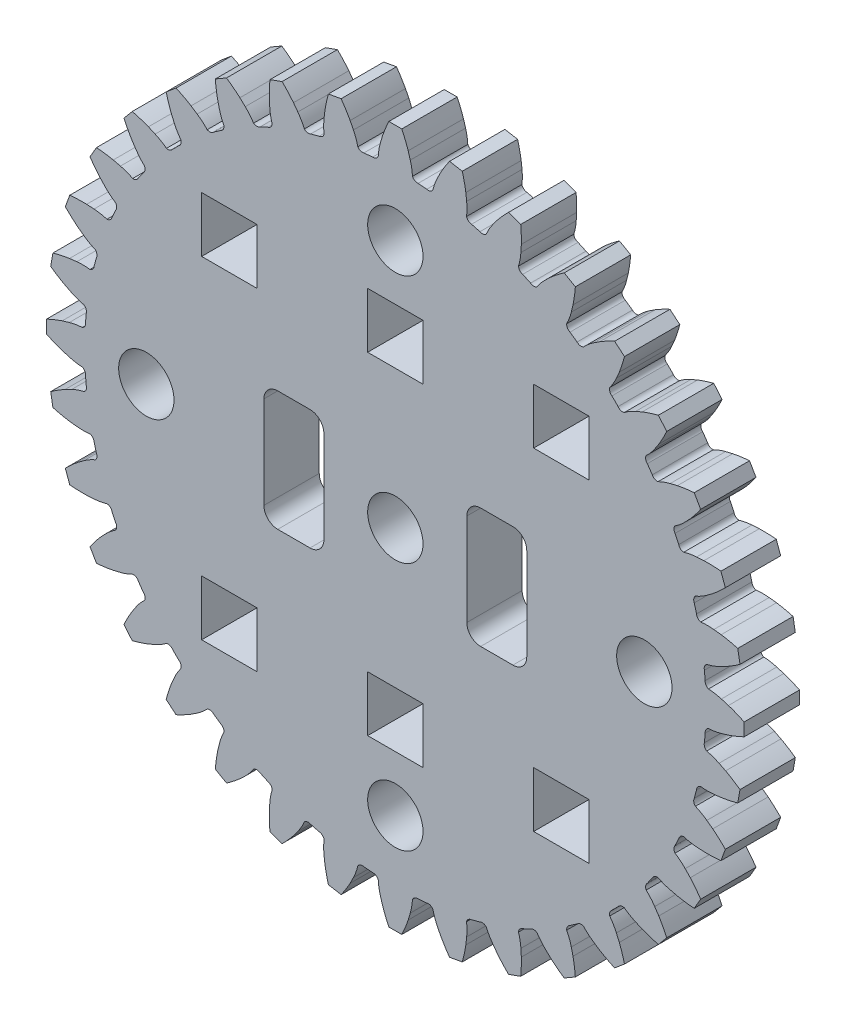
SolidWorks part; units mm, degrees
ref_plane "Alzado" through (0, 0, 0) normal (0, 0, 1) x (1, 0, 0)
ref_plane "Planta" through (0, 0, 0) normal (0, 1, 0) x (1, 0, 0)
ref_plane "Vista lateral" through (0, 0, 0) normal (1, 0, 0) x (0, 0, -1)
sketch "Model" plane through (0, 0, 0) normal (0, 0, 1) x (1, 0, 0)
  line L0 (33.2182, 284.4472) -> (33.2182, 281.4472)
  line L1 (36.2182, 284.4472) -> (33.2182, 284.4472)
  line L2 (36.2182, 281.4472) -> (36.2182, 284.4472)
  line L3 (33.2182, 281.4472) -> (36.2182, 281.4472)
  line L4 (15.2182, 284.4472) -> (15.2182, 281.4472)
  line L5 (18.2182, 284.4472) -> (15.2182, 284.4472)
  line L6 (18.2182, 281.4472) -> (18.2182, 284.4472)
  line L7 (15.2182, 281.4472) -> (18.2182, 281.4472)
  line L8 (24.2182, 284.4472) -> (24.2182, 281.4472)
  line L9 (27.2182, 284.4472) -> (24.2182, 284.4472)
  line L10 (27.2182, 281.4472) -> (27.2182, 284.4472)
  line L11 (24.2182, 281.4472) -> (27.2182, 281.4472)
  line L12 (33.2182, 266.4472) -> (33.2182, 263.4472)
  line L13 (36.2182, 266.4472) -> (33.2182, 266.4472)
  line L14 (36.2182, 263.4472) -> (36.2182, 266.4472)
  line L15 (33.2182, 263.4472) -> (36.2182, 263.4472)
  line L16 (15.2182, 266.4472) -> (15.2182, 263.4472)
  line L17 (18.2182, 266.4472) -> (15.2182, 266.4472)
  line L18 (18.2182, 263.4472) -> (18.2182, 266.4472)
  line L19 (15.2182, 263.4472) -> (18.2182, 263.4472)
  line L20 (24.2182, 266.4472) -> (24.2182, 263.4472)
  line L21 (27.2182, 266.4472) -> (24.2182, 266.4472)
  line L22 (27.2182, 263.4472) -> (27.2182, 266.4472)
  line L23 (24.2182, 263.4472) -> (27.2182, 263.4472)
  line L24 (31.0032, 290.8357) -> (31.2404, 291.1562)
  line L25 (31.8576, 291.8382) -> (32.5152, 291.5989)
  line L26 (32.5496, 290.6797) -> (32.5254, 290.2817)
  line L27 (32.6219, 289.3103) -> (33.0493, 289.111)
  line L28 (33.8556, 289.6614) -> (34.1448, 289.9358)
  line L29 (34.8711, 290.5003) -> (35.4771, 290.1504)
  line L30 (35.3514, 289.2392) -> (35.2584, 288.8515)
  line L31 (35.1848, 287.878) -> (35.5711, 287.6076)
  line L32 (36.4607, 288.0097) -> (36.7932, 288.2296)
  line L33 (37.6064, 288.6595) -> (38.1425, 288.2096)
  line L34 (37.8605, 287.3341) -> (37.7016, 286.9684)
  line L35 (37.4601, 286.0225) -> (37.7935, 285.6891)
  line L36 (38.7394, 285.9306) -> (39.1051, 286.0895)
  line L37 (39.9806, 286.3716) -> (40.4304, 285.8355)
  line L38 (40.0006, 285.0222) -> (39.7806, 284.6897)
  line L39 (39.3785, 283.8001) -> (39.649, 283.4138)
  line L40 (40.6225, 283.4874) -> (41.0102, 283.5804)
  line L41 (41.9214, 283.7062) -> (42.2713, 283.1001)
  line L42 (41.7068, 282.3739) -> (41.4324, 282.0846)
  line L43 (40.882, 281.2783) -> (41.0812, 280.851)
  line L44 (42.0527, 280.7544) -> (42.4507, 280.7786)
  line L45 (43.3699, 280.7442) -> (43.6092, 280.0866)
  line L46 (42.9272, 279.4694) -> (42.6067, 279.2322)
  line L47 (41.9246, 278.5338) -> (42.0467, 278.0783)
  line L48 (42.9866, 277.8145) -> (43.3827, 277.7693)
  line L49 (44.282, 277.5758) -> (44.4035, 276.8866)
  line L50 (43.6247, 276.3972) -> (43.2679, 276.2192)
  line L51 (42.4749, 275.6499) -> (42.516, 275.1801)
  line L52 (43.3958, 274.7571) -> (43.7781, 274.6438)
  line L53 (44.6301, 274.2971) -> (44.6301, 273.5973)
  line L54 (43.7781, 273.2506) -> (43.3958, 273.1373)
  line L55 (42.516, 272.7142) -> (42.4749, 272.2445)
  line L56 (43.2679, 271.6751) -> (43.6247, 271.4971)
  line L57 (44.4035, 271.0078) -> (44.282, 270.3186)
  line L58 (43.3827, 270.1251) -> (42.9866, 270.0799)
  line L59 (42.0467, 269.8161) -> (41.9246, 269.3606)
  line L60 (42.6067, 268.6622) -> (42.9272, 268.4249)
  line L61 (43.6092, 267.8077) -> (43.3699, 267.1501)
  line L62 (42.4507, 267.1157) -> (42.0527, 267.14)
  line L63 (41.0812, 267.0434) -> (40.882, 266.616)
  line L64 (41.4324, 265.8098) -> (41.7068, 265.5205)
  line L65 (42.2713, 264.7943) -> (41.9214, 264.1882)
  line L66 (41.0102, 264.3139) -> (40.6225, 264.4069)
  line L67 (39.649, 264.4805) -> (39.3785, 264.0942)
  line L68 (39.7806, 263.2047) -> (40.0006, 262.8721)
  line L69 (40.4304, 262.0589) -> (39.9806, 261.5228)
  line L70 (39.1051, 261.8049) -> (38.7394, 261.9638)
  line L71 (37.7935, 262.2053) -> (37.4601, 261.8718)
  line L72 (37.7016, 260.9259) -> (37.8605, 260.5603)
  line L73 (38.1425, 259.6847) -> (37.6064, 259.2349)
  line L74 (36.7932, 259.6647) -> (36.4607, 259.8847)
  line L75 (35.5711, 260.2868) -> (35.1848, 260.0163)
  line L76 (35.2584, 259.0429) -> (35.3514, 258.6552)
  line L77 (35.4771, 257.744) -> (34.8711, 257.394)
  line L78 (34.1448, 257.9585) -> (33.8556, 258.2329)
  line L79 (33.0493, 258.7834) -> (32.6219, 258.5841)
  line L80 (32.5254, 257.6127) -> (32.5496, 257.2147)
  line L81 (32.5152, 256.2955) -> (31.8576, 256.0561)
  line L82 (31.2404, 256.7382) -> (31.0032, 257.0586)
  line L83 (30.3048, 257.7407) -> (29.8493, 257.6187)
  line L84 (29.5855, 256.6788) -> (29.5403, 256.2826)
  line L85 (29.3468, 255.3834) -> (28.6576, 255.2618)
  line L86 (28.1682, 256.0407) -> (27.9902, 256.3975)
  line L87 (27.4209, 257.1905) -> (26.9511, 257.1494)
  line L88 (26.5281, 256.2695) -> (26.4148, 255.8873)
  line L89 (26.0681, 255.0353) -> (25.3682, 255.0353)
  line L90 (25.0215, 255.8873) -> (24.9082, 256.2695)
  line L91 (24.4852, 257.1494) -> (24.0155, 257.1905)
  line L92 (23.4461, 256.3975) -> (23.2681, 256.0407)
  line L93 (22.7787, 255.2618) -> (22.0895, 255.3834)
  line L94 (21.8961, 256.2826) -> (21.8508, 256.6788)
  line L95 (21.587, 257.6187) -> (21.1316, 257.7407)
  line L96 (20.4331, 257.0586) -> (20.1959, 256.7382)
  line L97 (19.5787, 256.0561) -> (18.9211, 256.2955)
  line L98 (18.8867, 257.2147) -> (18.911, 257.6127)
  line L99 (18.8144, 258.5841) -> (18.387, 258.7834)
  line L100 (17.5808, 258.2329) -> (17.2915, 257.9585)
  line L101 (16.5652, 257.394) -> (15.9592, 257.744)
  line L102 (16.0849, 258.6552) -> (16.1779, 259.0429)
  line L103 (16.2515, 260.0163) -> (15.8652, 260.2868)
  line L104 (14.9756, 259.8847) -> (14.6431, 259.6647)
  line L105 (13.8299, 259.2349) -> (13.2938, 259.6847)
  line L106 (13.5758, 260.5603) -> (13.7347, 260.9259)
  line L107 (13.9762, 261.8718) -> (13.6428, 262.2053)
  line L108 (12.6969, 261.9638) -> (12.3312, 261.8049)
  line L109 (11.4557, 261.5228) -> (11.0059, 262.0589)
  line L110 (11.4357, 262.8721) -> (11.6557, 263.2047)
  line L111 (12.0578, 264.0942) -> (11.7873, 264.4805)
  line L112 (10.8138, 264.4069) -> (10.4261, 264.3139)
  line L113 (9.5149, 264.1882) -> (9.165, 264.7943)
  line L114 (9.7295, 265.5205) -> (10.0039, 265.8098)
  line L115 (10.5544, 266.616) -> (10.3551, 267.0434)
  line L116 (9.3836, 267.14) -> (8.9857, 267.1157)
  line L117 (8.0665, 267.1501) -> (7.8271, 267.8077)
  line L118 (8.5091, 268.4249) -> (8.8296, 268.6622)
  line L119 (9.5117, 269.3606) -> (9.3896, 269.8161)
  line L120 (8.4497, 270.0799) -> (8.0536, 270.1251)
  line L121 (7.1543, 270.3186) -> (7.0328, 271.0078)
  line L122 (7.8117, 271.4971) -> (8.1684, 271.6751)
  line L123 (8.9614, 272.2445) -> (8.9203, 272.7142)
  line L124 (8.0405, 273.1373) -> (7.6582, 273.2506)
  line L125 (6.8063, 273.5973) -> (6.8063, 274.2971)
  line L126 (7.6582, 274.6438) -> (8.0405, 274.7571)
  line L127 (8.9203, 275.1801) -> (8.9614, 275.6499)
  line L128 (8.1684, 276.2192) -> (7.8117, 276.3972)
  line L129 (7.0328, 276.8866) -> (7.1543, 277.5758)
  line L130 (8.0536, 277.7693) -> (8.4497, 277.8145)
  line L131 (9.3896, 278.0783) -> (9.5117, 278.5338)
  line L132 (8.8296, 279.2322) -> (8.5091, 279.4694)
  line L133 (7.8271, 280.0866) -> (8.0665, 280.7442)
  line L134 (8.9857, 280.7786) -> (9.3836, 280.7544)
  line L135 (10.3551, 280.851) -> (10.5544, 281.2783)
  line L136 (10.0039, 282.0846) -> (9.7295, 282.3739)
  line L137 (9.165, 283.1001) -> (9.5149, 283.7062)
  line L138 (10.4261, 283.5804) -> (10.8138, 283.4874)
  line L139 (11.7873, 283.4138) -> (12.0578, 283.8001)
  line L140 (11.6557, 284.6897) -> (11.4357, 285.0222)
  line L141 (11.0059, 285.8355) -> (11.4557, 286.3716)
  line L142 (12.3312, 286.0895) -> (12.6969, 285.9306)
  line L143 (13.6428, 285.6891) -> (13.9762, 286.0225)
  line L144 (13.7347, 286.9684) -> (13.5758, 287.3341)
  line L145 (13.2938, 288.2096) -> (13.8299, 288.6595)
  line L146 (14.6431, 288.2296) -> (14.9756, 288.0097)
  line L147 (15.8652, 287.6076) -> (16.2515, 287.878)
  line L148 (16.1779, 288.8515) -> (16.0849, 289.2392)
  line L149 (15.9592, 290.1504) -> (16.5652, 290.5003)
  line L150 (17.2915, 289.9358) -> (17.5808, 289.6614)
  line L151 (18.387, 289.111) -> (18.8144, 289.3103)
  line L152 (18.911, 290.2817) -> (18.8867, 290.6797)
  line L153 (18.9211, 291.5989) -> (19.5787, 291.8382)
  line L154 (20.1959, 291.1562) -> (20.4331, 290.8357)
  line L155 (21.1316, 290.1537) -> (21.587, 290.2757)
  line L156 (21.8508, 291.2156) -> (21.8961, 291.6118)
  line L157 (22.0895, 292.511) -> (22.7787, 292.6325)
  line L158 (23.2681, 291.8537) -> (23.4461, 291.4969)
  line L159 (24.0155, 290.7039) -> (24.4852, 290.745)
  line L160 (24.9082, 291.6248) -> (25.0215, 292.0071)
  line L161 (25.3682, 292.8591) -> (26.0681, 292.8591)
  line L162 (26.4148, 292.0071) -> (26.5281, 291.6248)
  line L163 (26.9511, 290.745) -> (27.4209, 290.7039)
  line L164 (27.9902, 291.4969) -> (28.1682, 291.8537)
  line L165 (28.6576, 292.6325) -> (29.3468, 292.511)
  line L166 (29.5403, 291.6118) -> (29.5855, 291.2156)
  line L167 (29.8493, 290.2757) -> (30.3048, 290.1537)
  line L168 (32.0932, 277.1972) -> (30.3432, 277.1972)
  line L169 (32.8432, 271.4472) -> (32.8432, 276.4472)
  line L170 (30.3432, 270.6972) -> (32.0932, 270.6972)
  line L171 (29.5932, 276.4472) -> (29.5932, 271.4472)
  line L172 (19.3432, 277.1972) -> (21.0932, 277.1972)
  line L173 (18.5932, 271.4472) -> (18.5932, 276.4472)
  line L174 (21.0932, 270.6972) -> (19.3432, 270.6972)
  line L175 (21.8432, 276.4472) -> (21.8432, 271.4472)
  arc A0 (30.3048, 290.1537) -> (30.6516, 290.2156) centre (30.4356, 290.4233) ccw
  arc A1 (31.0032, 290.8357) -> (30.6516, 290.2156) centre (33.4432, 289.0429) ccw
  arc A2 (31.8576, 291.8382) -> (31.2404, 291.1562) centre (37.0183, 286.5478) ccw
  arc A3 (32.5496, 290.6797) -> (32.5152, 291.5989) centre (25.1612, 290.8634) ccw
  arc A4 (32.396, 289.5807) -> (32.5254, 290.2817) centre (29.5037, 290.4767) ccw
  arc A5 (32.396, 289.5807) -> (32.6219, 289.3103) centre (32.6951, 289.601) ccw
  arc A6 (33.0493, 289.111) -> (33.4017, 289.1117) centre (33.225, 289.3539) ccw
  arc A7 (33.8556, 289.6614) -> (33.4017, 289.1117) centre (35.9472, 287.4721) ccw
  arc A8 (34.8711, 290.5003) -> (34.1448, 289.9358) centre (39.0347, 284.3941) ccw
  arc A9 (35.3514, 289.2392) -> (35.4771, 290.1504) centre (28.1072, 290.7032) ccw
  arc A10 (35.0093, 288.1836) -> (35.2584, 288.8515) centre (32.3166, 289.5683) ccw
  arc A11 (35.0093, 288.1836) -> (35.1848, 287.878) centre (35.3073, 288.1516) ccw
  arc A12 (35.5711, 287.6076) -> (35.9182, 287.5471) centre (35.7863, 287.8162) ccw
  arc A13 (36.4607, 288.0097) -> (35.9182, 287.5471) centre (38.1404, 285.4904) ccw
  arc A14 (37.6064, 288.6595) -> (36.7932, 288.2296) centre (40.6465, 281.923) ccw
  arc A15 (37.8605, 287.3341) -> (38.1425, 288.2096) centre (30.9805, 290.0337) ccw
  arc A16 (37.3403, 286.3539) -> (37.7016, 286.9684) centre (34.9289, 288.1851) ccw
  arc A17 (37.3403, 286.3539) -> (37.4601, 286.0225) centre (37.6282, 286.2707) ccw
  arc A18 (37.7935, 285.6891) -> (38.1249, 285.5693) centre (38.0416, 285.8572) ccw
  arc A19 (38.7394, 285.9306) -> (38.1249, 285.5693) centre (39.9561, 283.1579) ccw
  arc A20 (39.9806, 286.3716) -> (39.1051, 286.0895) centre (41.8047, 279.2095) ccw
  arc A21 (40.0006, 285.0222) -> (40.4304, 285.8355) centre (33.694, 288.8756) ccw
  arc A22 (39.3181, 284.1473) -> (39.7806, 284.6897) centre (37.2614, 286.3694) ccw
  arc A23 (39.3181, 284.1473) -> (39.3785, 283.8001) centre (39.5872, 284.0153) ccw
  arc A24 (39.649, 283.4138) -> (39.9545, 283.2383) centre (39.9226, 283.5363) ccw
  arc A25 (40.6225, 283.4874) -> (39.9545, 283.2383) centre (41.3392, 280.5456) ccw
  arc A26 (41.9214, 283.7062) -> (41.0102, 283.5804) centre (42.4741, 276.3362) ccw
  arc A27 (41.7068, 282.3739) -> (42.2713, 283.1001) centre (36.1651, 287.2638) ccw
  arc A28 (40.8827, 281.6307) -> (41.4324, 282.0846) centre (39.2431, 284.1762) ccw
  arc A29 (40.8827, 281.6307) -> (40.882, 281.2783) centre (41.1248, 281.454) ccw
  arc A30 (41.0812, 280.851) -> (41.3517, 280.625) centre (41.3719, 280.9241) ccw
  arc A31 (42.0527, 280.7544) -> (41.3517, 280.625) centre (42.2477, 277.7328) ccw
  arc A32 (43.3699, 280.7442) -> (42.4507, 280.7786) centre (42.6344, 273.3903) ccw
  arc A33 (42.9272, 279.4694) -> (43.6092, 280.0866) centre (38.3188, 285.2474) ccw
  arc A34 (41.9866, 278.8807) -> (42.6067, 279.2322) centre (40.8139, 281.6723) ccw
  arc A35 (41.9866, 278.8807) -> (41.9246, 278.5338) centre (42.1943, 278.6646) ccw
  arc A36 (42.0467, 278.0783) -> (42.2737, 277.8089) centre (42.3456, 278.0998) ccw
  arc A37 (42.9866, 277.8145) -> (42.2737, 277.8089) centre (42.654, 274.8049) ccw
  arc A38 (44.282, 277.5758) -> (43.3827, 277.7693) centre (42.2807, 270.4612) ccw
  arc A39 (43.6247, 276.3972) -> (44.4035, 276.8866) centre (40.0896, 282.8876) ccw
  arc A40 (42.5961, 275.9807) -> (43.2679, 276.2192) centre (41.926, 278.9335) ccw
  arc A41 (42.5961, 275.9807) -> (42.4749, 275.6499) centre (42.7632, 275.7319) ccw
  arc A42 (42.516, 275.1801) -> (42.6928, 274.8753) centre (42.8141, 275.1494) ccw
  arc A43 (43.3958, 274.7571) -> (42.6928, 274.8753) centre (42.5456, 271.851) ccw
  arc A44 (44.6301, 274.2971) -> (43.7781, 274.6438) centre (41.4238, 267.6381) ccw
  arc A45 (43.7781, 273.2506) -> (44.6301, 273.5973) centre (41.4238, 280.2562) ccw
  arc A46 (42.6928, 273.019) -> (43.3958, 273.1373) centre (42.5456, 276.0433) ccw
  arc A47 (42.6928, 273.019) -> (42.516, 272.7142) centre (42.8141, 272.7449) ccw
  arc A48 (42.4749, 272.2445) -> (42.5961, 271.9136) centre (42.7632, 272.1625) ccw
  arc A49 (43.2679, 271.6751) -> (42.5961, 271.9136) centre (41.926, 268.9608) ccw
  arc A50 (44.4035, 271.0078) -> (43.6247, 271.4971) centre (40.0896, 265.0067) ccw
  arc A51 (43.3827, 270.1251) -> (44.282, 270.3186) centre (42.2807, 277.4331) ccw
  arc A52 (42.2737, 270.0855) -> (42.9866, 270.0799) centre (42.654, 273.0894) ccw
  arc A53 (42.2737, 270.0855) -> (42.0467, 269.8161) centre (42.3456, 269.7945) ccw
  arc A54 (41.9246, 269.3606) -> (41.9866, 269.0137) centre (42.1943, 269.2298) ccw
  arc A55 (42.6067, 268.6622) -> (41.9866, 269.0137) centre (40.8139, 266.2221) ccw
  arc A56 (43.6092, 267.8077) -> (42.9272, 268.4249) centre (38.3188, 262.647) ccw
  arc A57 (42.4507, 267.1157) -> (43.3699, 267.1501) centre (42.6344, 274.5041) ccw
  arc A58 (41.3517, 267.2693) -> (42.0527, 267.14) centre (42.2477, 270.1616) ccw
  arc A59 (41.3517, 267.2693) -> (41.0812, 267.0434) centre (41.3719, 266.9703) ccw
  arc A60 (40.882, 266.616) -> (40.8827, 266.2637) centre (41.1248, 266.4404) ccw
  arc A61 (41.4324, 265.8098) -> (40.8827, 266.2637) centre (39.2431, 263.7181) ccw
  arc A62 (42.2713, 264.7943) -> (41.7068, 265.5205) centre (36.1651, 260.6306) ccw
  arc A63 (41.0102, 264.3139) -> (41.9214, 264.1882) centre (42.4741, 271.5582) ccw
  arc A64 (39.9545, 264.6561) -> (40.6225, 264.4069) centre (41.3392, 267.3488) ccw
  arc A65 (39.9545, 264.6561) -> (39.649, 264.4805) centre (39.9226, 264.358) ccw
  arc A66 (39.3785, 264.0942) -> (39.3181, 263.7471) centre (39.5872, 263.8791) ccw
  arc A67 (39.7806, 263.2047) -> (39.3181, 263.7471) centre (37.2614, 261.525) ccw
  arc A68 (40.4304, 262.0589) -> (40.0006, 262.8721) centre (33.694, 259.0188) ccw
  arc A69 (39.1051, 261.8049) -> (39.9806, 261.5228) centre (41.8047, 268.6848) ccw
  arc A70 (38.1249, 262.3251) -> (38.7394, 261.9638) centre (39.9561, 264.7364) ccw
  arc A71 (38.1249, 262.3251) -> (37.7935, 262.2053) centre (38.0416, 262.0371) ccw
  arc A72 (37.4601, 261.8718) -> (37.3403, 261.5405) centre (37.6282, 261.6237) ccw
  arc A73 (37.7016, 260.9259) -> (37.3403, 261.5405) centre (34.9289, 259.7092) ccw
  arc A74 (38.1425, 259.6847) -> (37.8605, 260.5603) centre (30.9805, 257.8606) ccw
  arc A75 (36.7932, 259.6647) -> (37.6064, 259.2349) centre (40.6465, 265.9714) ccw
  arc A76 (35.9182, 260.3472) -> (36.4607, 259.8847) centre (38.1404, 262.404) ccw
  arc A77 (35.9182, 260.3472) -> (35.5711, 260.2868) centre (35.7863, 260.0781) ccw
  arc A78 (35.1848, 260.0163) -> (35.0093, 259.7108) centre (35.3073, 259.7428) ccw
  arc A79 (35.2584, 259.0429) -> (35.0093, 259.7108) centre (32.3166, 258.3261) ccw
  arc A80 (35.4771, 257.744) -> (35.3514, 258.6552) centre (28.1072, 257.1912) ccw
  arc A81 (34.1448, 257.9585) -> (34.8711, 257.394) centre (39.0347, 263.5003) ccw
  arc A82 (33.4017, 258.7826) -> (33.8556, 258.2329) centre (35.9472, 260.4223) ccw
  arc A83 (33.4017, 258.7826) -> (33.0493, 258.7834) centre (33.225, 258.5405) ccw
  arc A84 (32.6219, 258.5841) -> (32.396, 258.3137) centre (32.6951, 258.2934) ccw
  arc A85 (32.5254, 257.6127) -> (32.396, 258.3137) centre (29.5037, 257.4176) ccw
  arc A86 (32.5152, 256.2955) -> (32.5496, 257.2147) centre (25.1612, 257.0309) ccw
  arc A87 (31.2404, 256.7382) -> (31.8576, 256.0561) centre (37.0183, 261.3466) ccw
  arc A88 (30.6516, 257.6788) -> (31.0032, 257.0586) centre (33.4432, 258.8515) ccw
  arc A89 (30.6516, 257.6788) -> (30.3048, 257.7407) centre (30.4356, 257.471) ccw
  arc A90 (29.8493, 257.6187) -> (29.5798, 257.3916) centre (29.8708, 257.3197) ccw
  arc A91 (29.5855, 256.6788) -> (29.5798, 257.3916) centre (26.5759, 257.0114) ccw
  arc A92 (29.3468, 255.3834) -> (29.5403, 256.2826) centre (22.2322, 257.3846) ccw
  arc A93 (28.1682, 256.0407) -> (28.6576, 255.2618) centre (34.6586, 259.5757) ccw
  arc A94 (27.7517, 257.0692) -> (27.9902, 256.3975) centre (30.7045, 257.7394) ccw
  arc A95 (27.7517, 257.0692) -> (27.4209, 257.1905) centre (27.5029, 256.9022) ccw
  arc A96 (26.9511, 257.1494) -> (26.6463, 256.9725) centre (26.9204, 256.8512) ccw
  arc A97 (26.5281, 256.2695) -> (26.6463, 256.9725) centre (23.622, 257.1197) ccw
  arc A98 (26.0681, 255.0353) -> (26.4148, 255.8873) centre (19.4091, 258.2416) ccw
  arc A99 (25.0215, 255.8873) -> (25.3682, 255.0353) centre (32.0272, 258.2416) ccw
  arc A100 (24.79, 256.9725) -> (24.9082, 256.2695) centre (27.8143, 257.1197) ccw
  arc A101 (24.79, 256.9725) -> (24.4852, 257.1494) centre (24.5159, 256.8512) ccw
  arc A102 (24.0155, 257.1905) -> (23.6846, 257.0692) centre (23.9335, 256.9022) ccw
  arc A103 (23.4461, 256.3975) -> (23.6846, 257.0692) centre (20.7318, 257.7394) ccw
  arc A104 (22.7787, 255.2618) -> (23.2681, 256.0407) centre (16.7777, 259.5757) ccw
  arc A105 (21.8961, 256.2826) -> (22.0895, 255.3834) centre (29.2041, 257.3846) ccw
  arc A106 (21.8565, 257.3916) -> (21.8508, 256.6788) centre (24.8604, 257.0114) ccw
  arc A107 (21.8565, 257.3916) -> (21.587, 257.6187) centre (21.5655, 257.3197) ccw
  arc A108 (21.1316, 257.7407) -> (20.7847, 257.6788) centre (21.0007, 257.471) ccw
  arc A109 (20.4331, 257.0586) -> (20.7847, 257.6788) centre (17.9931, 258.8515) ccw
  arc A110 (19.5787, 256.0561) -> (20.1959, 256.7382) centre (14.418, 261.3466) ccw
  arc A111 (18.8867, 257.2147) -> (18.9211, 256.2955) centre (26.2751, 257.0309) ccw
  arc A112 (19.0403, 258.3137) -> (18.911, 257.6127) centre (21.9326, 257.4176) ccw
  arc A113 (19.0403, 258.3137) -> (18.8144, 258.5841) centre (18.7412, 258.2934) ccw
  arc A114 (18.387, 258.7834) -> (18.0346, 258.7826) centre (18.2113, 258.5405) ccw
  arc A115 (17.5808, 258.2329) -> (18.0346, 258.7826) centre (15.4891, 260.4223) ccw
  arc A116 (16.5652, 257.394) -> (17.2915, 257.9585) centre (12.4016, 263.5003) ccw
  arc A117 (16.0849, 258.6552) -> (15.9592, 257.744) centre (23.3291, 257.1912) ccw
  arc A118 (16.427, 259.7108) -> (16.1779, 259.0429) centre (19.1197, 258.3261) ccw
  arc A119 (16.427, 259.7108) -> (16.2515, 260.0163) centre (16.129, 259.7428) ccw
  arc A120 (15.8652, 260.2868) -> (15.5181, 260.3472) centre (15.65, 260.0781) ccw
  arc A121 (14.9756, 259.8847) -> (15.5181, 260.3472) centre (13.2959, 262.404) ccw
  arc A122 (13.8299, 259.2349) -> (14.6431, 259.6647) centre (10.7898, 265.9714) ccw
  arc A123 (13.5758, 260.5603) -> (13.2938, 259.6847) centre (20.4558, 257.8606) ccw
  arc A124 (14.0961, 261.5405) -> (13.7347, 260.9259) centre (16.5074, 259.7092) ccw
  arc A125 (14.0961, 261.5405) -> (13.9762, 261.8718) centre (13.8081, 261.6237) ccw
  arc A126 (13.6428, 262.2053) -> (13.3114, 262.3251) centre (13.3947, 262.0371) ccw
  arc A127 (12.6969, 261.9638) -> (13.3114, 262.3251) centre (11.4802, 264.7364) ccw
  arc A128 (11.4557, 261.5228) -> (12.3312, 261.8049) centre (9.6316, 268.6848) ccw
  arc A129 (11.4357, 262.8721) -> (11.0059, 262.0589) centre (17.7423, 259.0188) ccw
  arc A130 (12.1182, 263.7471) -> (11.6557, 263.2047) centre (14.175, 261.525) ccw
  arc A131 (12.1182, 263.7471) -> (12.0578, 264.0942) centre (11.8491, 263.8791) ccw
  arc A132 (11.7873, 264.4805) -> (11.4818, 264.6561) centre (11.5137, 264.358) ccw
  arc A133 (10.8138, 264.4069) -> (11.4818, 264.6561) centre (10.0971, 267.3488) ccw
  arc A134 (9.5149, 264.1882) -> (10.4261, 264.3139) centre (8.9622, 271.5582) ccw
  arc A135 (9.7295, 265.5205) -> (9.165, 264.7943) centre (15.2712, 260.6306) ccw
  arc A136 (10.5536, 266.2637) -> (10.0039, 265.8098) centre (12.1932, 263.7181) ccw
  arc A137 (10.5536, 266.2637) -> (10.5544, 266.616) centre (10.3115, 266.4404) ccw
  arc A138 (10.3551, 267.0434) -> (10.0847, 267.2693) centre (10.0644, 266.9703) ccw
  arc A139 (9.3836, 267.14) -> (10.0847, 267.2693) centre (9.1886, 270.1616) ccw
  arc A140 (8.0665, 267.1501) -> (8.9857, 267.1157) centre (8.8019, 274.5041) ccw
  arc A141 (8.5091, 268.4249) -> (7.8271, 267.8077) centre (13.1175, 262.647) ccw
  arc A142 (9.4498, 269.0137) -> (8.8296, 268.6622) centre (10.6224, 266.2221) ccw
  arc A143 (9.4498, 269.0137) -> (9.5117, 269.3606) centre (9.242, 269.2298) ccw
  arc A144 (9.3896, 269.8161) -> (9.1626, 270.0855) centre (9.0907, 269.7945) ccw
  arc A145 (8.4497, 270.0799) -> (9.1626, 270.0855) centre (8.7824, 273.0894) ccw
  arc A146 (7.1543, 270.3186) -> (8.0536, 270.1251) centre (9.1556, 277.4331) ccw
  arc A147 (7.8117, 271.4971) -> (7.0328, 271.0078) centre (11.3467, 265.0067) ccw
  arc A148 (8.8402, 271.9136) -> (8.1684, 271.6751) centre (9.5103, 268.9608) ccw
  arc A149 (8.8402, 271.9136) -> (8.9614, 272.2445) centre (8.6731, 272.1625) ccw
  arc A150 (8.9203, 272.7142) -> (8.7435, 273.019) centre (8.6222, 272.7449) ccw
  arc A151 (8.0405, 273.1373) -> (8.7435, 273.019) centre (8.8907, 276.0433) ccw
  arc A152 (6.8063, 273.5973) -> (7.6582, 273.2506) centre (10.0126, 280.2562) ccw
  arc A153 (7.6582, 274.6438) -> (6.8063, 274.2971) centre (10.0126, 267.6381) ccw
  arc A154 (8.7435, 274.8753) -> (8.0405, 274.7571) centre (8.8907, 271.851) ccw
  arc A155 (8.7435, 274.8753) -> (8.9203, 275.1801) centre (8.6222, 275.1494) ccw
  arc A156 (8.9614, 275.6499) -> (8.8402, 275.9807) centre (8.6731, 275.7319) ccw
  arc A157 (8.1684, 276.2192) -> (8.8402, 275.9807) centre (9.5103, 278.9335) ccw
  arc A158 (7.0328, 276.8866) -> (7.8117, 276.3972) centre (11.3467, 282.8876) ccw
  arc A159 (8.0536, 277.7693) -> (7.1543, 277.5758) centre (9.1556, 270.4612) ccw
  arc A160 (9.1626, 277.8089) -> (8.4497, 277.8145) centre (8.7824, 274.8049) ccw
  arc A161 (9.1626, 277.8089) -> (9.3896, 278.0783) centre (9.0907, 278.0998) ccw
  arc A162 (9.5117, 278.5338) -> (9.4498, 278.8807) centre (9.242, 278.6646) ccw
  arc A163 (8.8296, 279.2322) -> (9.4498, 278.8807) centre (10.6224, 281.6723) ccw
  arc A164 (7.8271, 280.0866) -> (8.5091, 279.4694) centre (13.1175, 285.2474) ccw
  arc A165 (8.9857, 280.7786) -> (8.0665, 280.7442) centre (8.8019, 273.3903) ccw
  arc A166 (10.0847, 280.625) -> (9.3836, 280.7544) centre (9.1886, 277.7328) ccw
  arc A167 (10.0847, 280.625) -> (10.3551, 280.851) centre (10.0644, 280.9241) ccw
  arc A168 (10.5544, 281.2783) -> (10.5536, 281.6307) centre (10.3115, 281.454) ccw
  arc A169 (10.0039, 282.0846) -> (10.5536, 281.6307) centre (12.1932, 284.1762) ccw
  arc A170 (9.165, 283.1001) -> (9.7295, 282.3739) centre (15.2712, 287.2638) ccw
  arc A171 (10.4261, 283.5804) -> (9.5149, 283.7062) centre (8.9622, 276.3362) ccw
  arc A172 (11.4818, 283.2383) -> (10.8138, 283.4874) centre (10.0971, 280.5456) ccw
  arc A173 (11.4818, 283.2383) -> (11.7873, 283.4138) centre (11.5137, 283.5363) ccw
  arc A174 (12.0578, 283.8001) -> (12.1182, 284.1473) centre (11.8491, 284.0153) ccw
  arc A175 (11.6557, 284.6897) -> (12.1182, 284.1473) centre (14.175, 286.3694) ccw
  arc A176 (11.0059, 285.8355) -> (11.4357, 285.0222) centre (17.7423, 288.8756) ccw
  arc A177 (12.3312, 286.0895) -> (11.4557, 286.3716) centre (9.6316, 279.2095) ccw
  arc A178 (13.3114, 285.5693) -> (12.6969, 285.9306) centre (11.4802, 283.1579) ccw
  arc A179 (13.3114, 285.5693) -> (13.6428, 285.6891) centre (13.3947, 285.8572) ccw
  arc A180 (13.9762, 286.0225) -> (14.0961, 286.3539) centre (13.8081, 286.2707) ccw
  arc A181 (13.7347, 286.9684) -> (14.0961, 286.3539) centre (16.5074, 288.1851) ccw
  arc A182 (13.2938, 288.2096) -> (13.5758, 287.3341) centre (20.4558, 290.0337) ccw
  arc A183 (14.6431, 288.2296) -> (13.8299, 288.6595) centre (10.7898, 281.923) ccw
  arc A184 (15.5181, 287.5471) -> (14.9756, 288.0097) centre (13.2959, 285.4904) ccw
  arc A185 (15.5181, 287.5471) -> (15.8652, 287.6076) centre (15.65, 287.8162) ccw
  arc A186 (16.2515, 287.878) -> (16.427, 288.1836) centre (16.129, 288.1516) ccw
  arc A187 (16.1779, 288.8515) -> (16.427, 288.1836) centre (19.1197, 289.5683) ccw
  arc A188 (15.9592, 290.1504) -> (16.0849, 289.2392) centre (23.3291, 290.7032) ccw
  arc A189 (17.2915, 289.9358) -> (16.5652, 290.5003) centre (12.4016, 284.3941) ccw
  arc A190 (18.0346, 289.1117) -> (17.5808, 289.6614) centre (15.4891, 287.4721) ccw
  arc A191 (18.0346, 289.1117) -> (18.387, 289.111) centre (18.2113, 289.3539) ccw
  arc A192 (18.8144, 289.3103) -> (19.0403, 289.5807) centre (18.7412, 289.601) ccw
  arc A193 (18.911, 290.2817) -> (19.0403, 289.5807) centre (21.9326, 290.4767) ccw
  arc A194 (18.9211, 291.5989) -> (18.8867, 290.6797) centre (26.2751, 290.8634) ccw
  arc A195 (20.1959, 291.1562) -> (19.5787, 291.8382) centre (14.418, 286.5478) ccw
  arc A196 (20.7847, 290.2156) -> (20.4331, 290.8357) centre (17.9931, 289.0429) ccw
  arc A197 (20.7847, 290.2156) -> (21.1316, 290.1537) centre (21.0007, 290.4233) ccw
  arc A198 (21.587, 290.2757) -> (21.8565, 290.5028) centre (21.5655, 290.5747) ccw
  arc A199 (21.8508, 291.2156) -> (21.8565, 290.5028) centre (24.8604, 290.883) ccw
  arc A200 (22.0895, 292.511) -> (21.8961, 291.6118) centre (29.2041, 290.5097) ccw
  arc A201 (23.2681, 291.8537) -> (22.7787, 292.6325) centre (16.7777, 288.3186) ccw
  arc A202 (23.6846, 290.8251) -> (23.4461, 291.4969) centre (20.7318, 290.155) ccw
  arc A203 (23.6846, 290.8251) -> (24.0155, 290.7039) centre (23.9335, 290.9922) ccw
  arc A204 (24.4852, 290.745) -> (24.79, 290.9218) centre (24.5159, 291.0432) ccw
  arc A205 (24.9082, 291.6248) -> (24.79, 290.9218) centre (27.8143, 290.7746) ccw
  arc A206 (25.3682, 292.8591) -> (25.0215, 292.0071) centre (32.0272, 289.6528) ccw
  arc A207 (26.4148, 292.0071) -> (26.0681, 292.8591) centre (19.4091, 289.6528) ccw
  arc A208 (26.6463, 290.9218) -> (26.5281, 291.6248) centre (23.622, 290.7746) ccw
  arc A209 (26.6463, 290.9218) -> (26.9511, 290.745) centre (26.9204, 291.0432) ccw
  arc A210 (27.4209, 290.7039) -> (27.7517, 290.8251) centre (27.5029, 290.9922) ccw
  arc A211 (27.9902, 291.4969) -> (27.7517, 290.8251) centre (30.7045, 290.155) ccw
  arc A212 (28.6576, 292.6325) -> (28.1682, 291.8537) centre (34.6586, 288.3186) ccw
  arc A213 (29.5403, 291.6118) -> (29.3468, 292.511) centre (22.2322, 290.5097) ccw
  arc A214 (29.5798, 290.5028) -> (29.5855, 291.2156) centre (26.5759, 290.883) ccw
  arc A215 (29.5798, 290.5028) -> (29.8493, 290.2757) centre (29.8708, 290.5747) ccw
  circle A216 centre (39.2182, 273.9472) radius 1.5
  arc A217 (30.3432, 277.1972) -> (29.5932, 276.4472) centre (30.3432, 276.4472) ccw
  arc A218 (32.8432, 276.4472) -> (32.0932, 277.1972) centre (32.0932, 276.4472) ccw
  arc A219 (32.0932, 270.6972) -> (32.8432, 271.4472) centre (32.0932, 271.4472) ccw
  arc A220 (29.5932, 271.4472) -> (30.3432, 270.6972) centre (30.3432, 271.4472) ccw
  arc A221 (21.8432, 276.4472) -> (21.0932, 277.1972) centre (21.0932, 276.4472) ccw
  arc A222 (19.3432, 277.1972) -> (18.5932, 276.4472) centre (19.3432, 276.4472) ccw
  arc A223 (18.5932, 271.4472) -> (19.3432, 270.6972) centre (19.3432, 271.4472) ccw
  arc A224 (21.0932, 270.6972) -> (21.8432, 271.4472) centre (21.0932, 271.4472) ccw
  circle A225 centre (25.7182, 273.9472) radius 1.5
  circle A226 centre (12.2182, 273.9472) radius 1.5
  circle A227 centre (25.7182, 260.4472) radius 1.5
  circle A228 centre (25.7182, 287.4472) radius 1.5
extrude "Saliente-Extruir1" add sketch "Model" along normal blind 3
